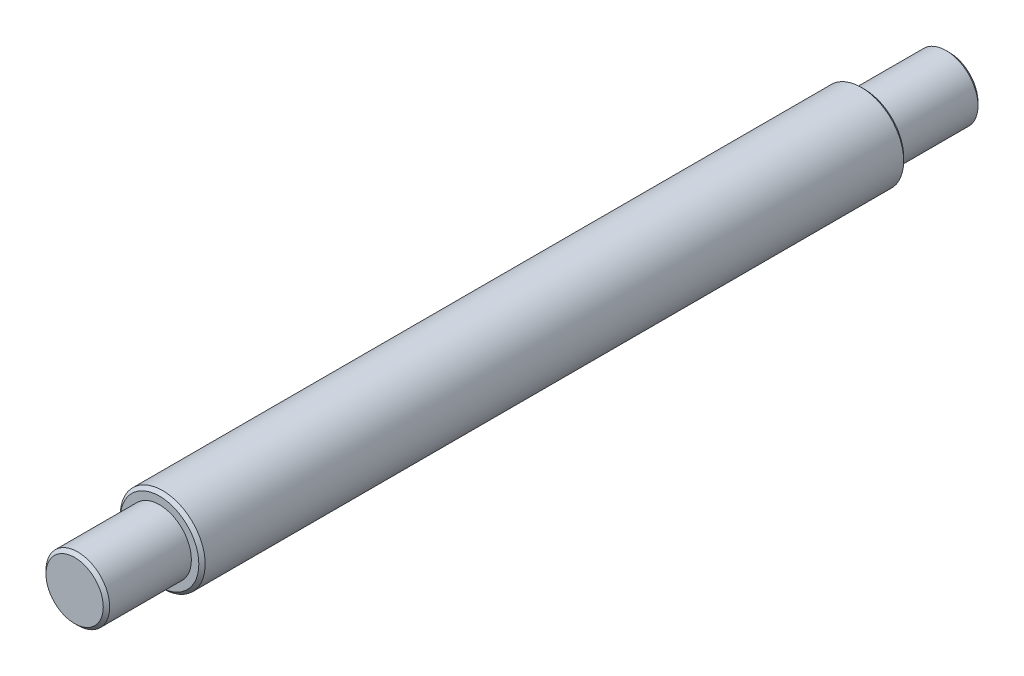
SolidWorks part; units mm, degrees
ref_plane "Front Plane" through (0, 0, 0) normal (0, 0, 1) x (1, 0, 0)
ref_plane "Top Plane" through (0, 0, 0) normal (0, 1, 0) x (1, 0, 0)
ref_plane "Right Plane" through (0, 0, 0) normal (1, 0, 0) x (0, 0, -1)
sketch "Sketch1" plane through (0, 0, 0) normal (0, 0, 1) x (1, 0, 0)
  circle A0 centre (0, 0) radius 4
  dimension "D1" = 8
extrude "Boss-Extrude1" add sketch "Sketch1" along normal mid plane 66.4
sketch "Sketch2" plane through (0, 0, 33.2) normal (0, 0, 1) x (1, 0, 0)
  circle A0 centre (0, 0) radius 3
  dimension "D1" = 6
extrude "Boss-Extrude2" add sketch "Sketch2" along normal blind 8
mirror "Mirror1" about plane through (0, 0, 0) normal (0, 0, 1) of "Boss-Extrude2"
chamfer "Chamfer1" distance 0.3 angle 45 4 edges at (3, 0, -41.2) (4, 0, -33.2) (4, 0, 33.2) (3, 0, 41.2)
